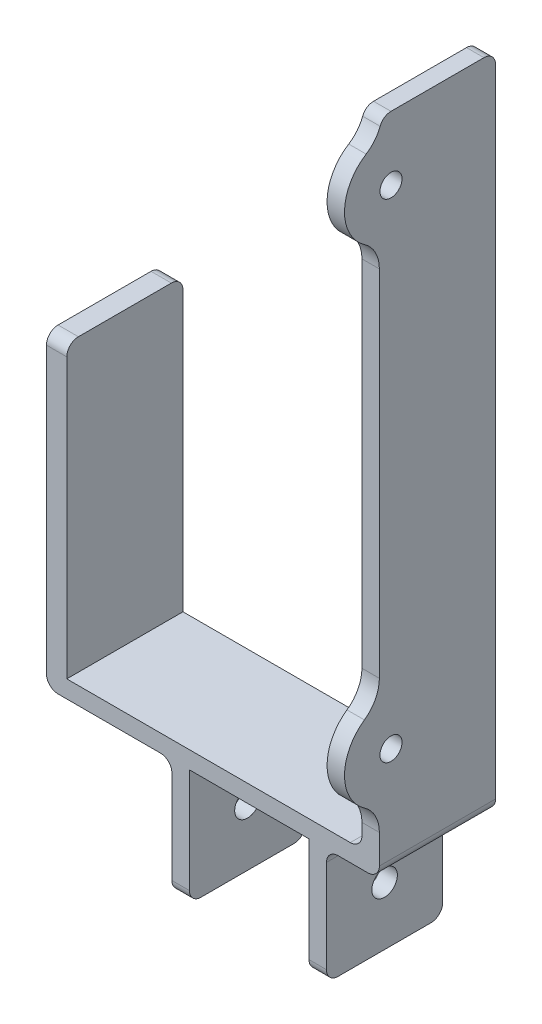
SolidWorks part; units mm, degrees
material "ABS"
ref_plane "Front Plane" through (0, 0, 0) normal (0, 0, 1) x (1, 0, 0)
ref_plane "Top Plane" through (0, 0, 0) normal (0, 1, 0) x (1, 0, 0)
ref_plane "Right Plane" through (0, 0, 0) normal (1, 0, 0) x (0, 0, -1)
sketch "Sketch1" plane through (0, 0, 0) normal (0, 0, 1) x (1, 0, 0)
  line L0 (-25.4, 0) -> (25.4, 0)
  line L1 (25.4, 0) -> (25.4, 110.5)
  line L2 (25.4, 110.5) -> (28.4, 110.5)
  line L3 (28.4, 110.5) -> (28.4, -3)
  line L4 (28.4, -3) -> (19.3, -3)
  line L5 (-28.9, -3) -> (-28.9, 50)
  line L6 (-28.9, 50) -> (-25.4, 50)
  line L7 (-25.4, 50) -> (-25.4, 0)
  line L8 (-4.3, -23) -> (-4.3, -3)
  line L9 (-4.3, -23) -> (-7.3, -23)
  line L10 (-7.3, -23) -> (-7.3, -3)
  line L11 (16.3, -3) -> (16.3, -23)
  line L12 (16.3, -23) -> (19.3, -23)
  line L13 (19.3, -23) -> (19.3, -3)
  line L14 (-7.3, -3) -> (-28.9, -3)
  line L15 (16.3, -3) -> (-4.3, -3)
  dimension "D1" = 50.8
  dimension "D2" = 110.5
  dimension "D3" = 50
  dimension "D4" = 3
  dimension "D5" = 3.5
  dimension "D6" = 3
  dimension "D7" = 20.6
  dimension "D8" = 3
  dimension "D9" = 20
  dimension "D10" = 21.6
extrude "Boss-Extrude1" add sketch "Sketch1" along normal blind 20
sketch "Sketch2" plane through (19.3, 0, 0) normal (1, 0, 0) x (0, 0, -1)
  line L0 (-10, -13) -> (-10, -23) construction
  line L1 (-20, -23) -> (0, -23) construction
  circle A0 centre (-10, -13) radius 2.2
  dimension "D2" = 4.4
  dimension "D1" = 10
extrude "Cut-Extrude1" cut sketch "Sketch2" against normal through all
sketch "Sketch3" plane through (28.4, 0, 0) normal (1, 0, 0) x (0, 0, -1)
  line L0 (0, -3) -> (0, 110.5) construction
  line L1 (-20, 110.5) -> (0, 110.5) construction
  circle A0 centre (-18, 99.5) radius 8
  circle A1 centre (-18, 15.5) radius 8
  dimension "D1" = 16
  dimension "D2" = 18
  dimension "D3" = 84
  dimension "D4" = 11
extrude "Boss-Extrude2" add sketch "Sketch3" against normal up to surface (3 mm away) up to face at (25.4, 55.25, 10)
sketch "Sketch4" plane through (28.4, 0, 0) normal (1, 0, 0) x (0, 0, -1)
  circle A0 centre (-18, 99.5) radius 1.9
  circle A1 centre (-18, 15.5) radius 1.9
  dimension "D1" = 3.8
extrude "Cut-Extrude2" cut sketch "Sketch4" against normal up to next
fillet "Fillet1" radius 2 13 edges at (-27.15, 50, 0) (-27.15, 50, 20) (-28.9, -3, 10) (17.8, -23, 20) (17.8, -23, 0) (-5.8, -23, 0) (-5.8, -23, 20) (-7.3, -3, 10) (19.3, -3, 10) (28.4, -3, 10) (26.9, 110.5, 0) (26.9, 110.5, 20) (25.4, 0, 10)
fillet "Fillet2" radius 6 4 edges at (26.9, 91.754, 20) (26.9, 107.246, 20) (26.9, 7.754, 20) (26.9, 23.246, 20)
